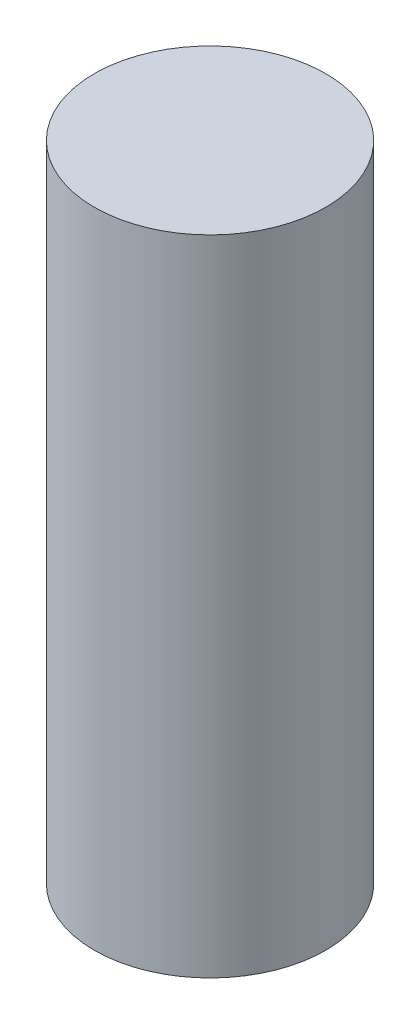
SolidWorks part; units mm, degrees
ref_plane "Front Plane" through (0, 0, 0) normal (0, 0, 1) x (1, 0, 0)
ref_plane "Top Plane" through (0, 0, 0) normal (0, 1, 0) x (1, 0, 0)
ref_plane "Right Plane" through (0, 0, 0) normal (1, 0, 0) x (0, 0, -1)
sketch "Sketch1" plane through (0, 0, 0) normal (0, 1, 0) x (1, 0, 0)
  circle A0 centre (0, 0) radius 4
  dimension "D1" = 8
extrude "Boss-Extrude1" add sketch "Sketch1" along normal blind 22.24
